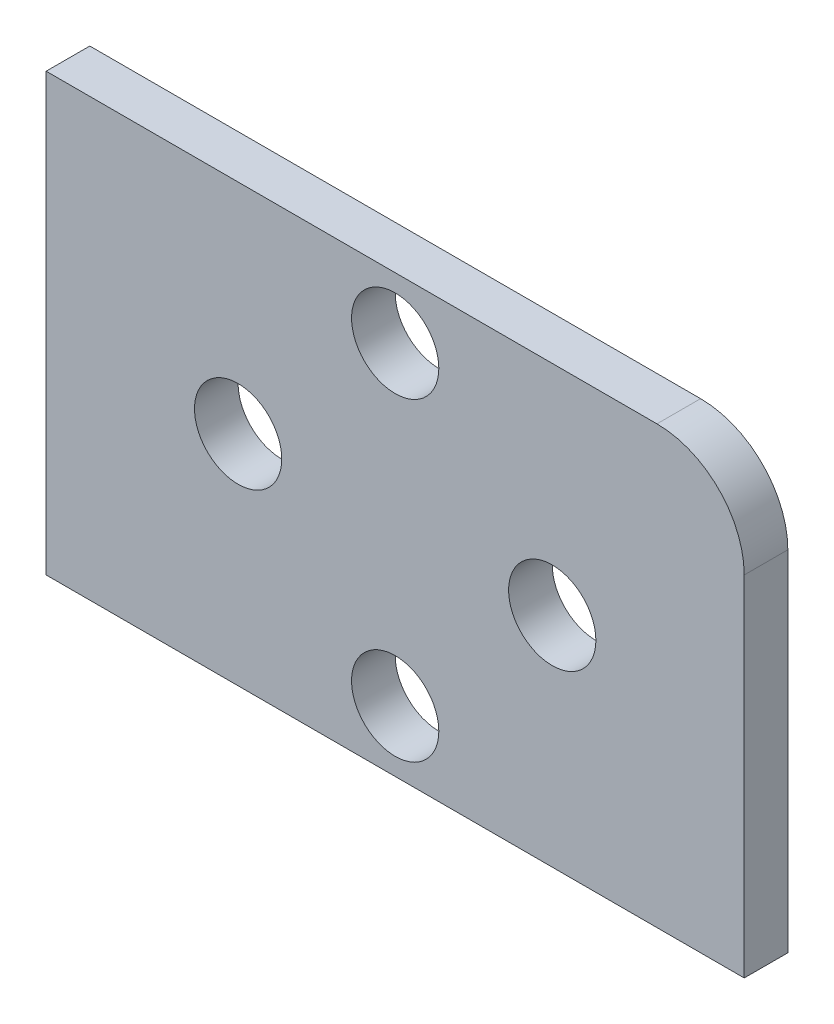
SolidWorks part; units mm, degrees
ref_plane "Front Plane" through (0, 0, 0) normal (0, 0, 1) x (1, 0, 0)
ref_plane "Top Plane" through (0, 0, 0) normal (0, 1, 0) x (1, 0, 0)
ref_plane "Right Plane" through (0, 0, 0) normal (1, 0, 0) x (0, 0, -1)
sketch "Sketch2" plane through (0, 0, 0) normal (0, 0, 1) x (1, 0, 0)
  line L0 (0, 0) -> (40, 0)
  line L1 (40, 0) -> (40, 25)
  line L2 (0, 0) -> (-18, 0)
  line L3 (40, 25) -> (-40, 25)
  line L4 (40, 25) -> (40, -25)
  line L5 (40, -25) -> (-40, -25)
  line L6 (-40, 25) -> (-40, -25)
  circle A4 centre (-18, 0) radius 5
  point P18 (0, 0)
  dimension "D1" = 40
  dimension "D2" = 25
  dimension "D3" = 80
  dimension "D4" = 50
  dimension "D5" = 18
extrude "Boss-Extrude1" add sketch "Sketch2" against normal blind 5 contours L4 L5 L6 L3
sketch "Sketch3" plane through (0, 0, 0) normal (0, 0, 1) x (1, 0, 0)
  line L0 (0, 0) -> (-18, 0)
  circle A0 centre (-18, 0) radius 5
  circle A1 centre (0, 18) radius 5
  circle A2 centre (18, 0) radius 5
  circle A3 centre (0, -18) radius 5
  point P13 (0, 0)
  dimension "D2" = 4
  dimension "D1" = 18
extrude "Cut-Extrude1" cut sketch "Sketch3" against normal blind 5
sketch "Sketch4" plane through (0, 0, 0) normal (0, 0, 1) x (1, 0, 0)
  line L0 (54.0269, -3.11) -> (74.9267, -3.11)
  line L1 (74.9267, -3.11) -> (74.9267, 30.9896)
  line L2 (74.9267, 30.9896) -> (54.0269, 30.9896)
  line L3 (54.0269, 30.9896) -> (54.0269, -3.11)
fillet "Fillet1" radius 10 1 edges at (40, 25, -2.5)
